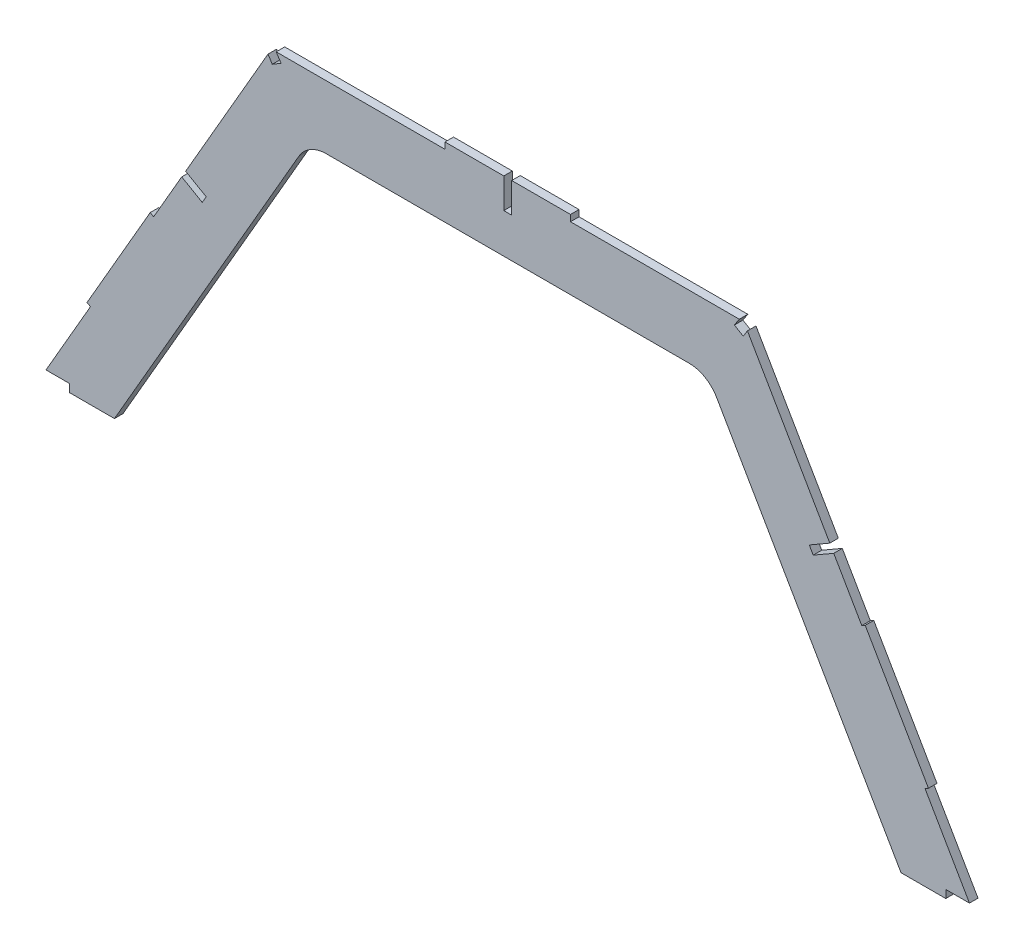
SolidWorks part; units mm, degrees
material "Balsa"
ref_plane "Front Plane" through (0, 0, 0) normal (0, 0, 1) x (1, 0, 0)
ref_plane "Top Plane" through (0, 0, 0) normal (0, 1, 0) x (1, 0, 0)
ref_plane "Right Plane" through (0, 0, 0) normal (1, 0, 0) x (0, 0, -1)
sketch "Sketch1" plane through (0, 0, 0) normal (0, 0, 1) x (1, 0, 0)
  line L0 (-196.85, 0) -> (-63.5, 230.969)
  line L1 (-63.5, 230.969) -> (63.5, 230.969)
  line L2 (63.5, 230.969) -> (196.85, 0)
  line L9 (-167.5206, 0) -> (-48.8353, 205.569)
  line L10 (-48.8353, 205.569) -> (48.8353, 205.569)
  line L11 (48.8353, 205.569) -> (167.5206, 0)
  line L12 (-196.85, 0) -> (-167.5206, 0)
  line L13 (196.85, 0) -> (167.5206, 0)
  line L14 (-174.853, -12.7) -> (-48.8353, 205.569) construction
  line L15 (48.8353, 205.569) -> (174.853, -12.7) construction
  point P14 (0, 205.569)
  dimension "D1" = 127
  dimension "D2" = 120
  dimension "D3" = 25.4
  dimension "D4" = 266.7
  dimension "D5" = 266.7
extrude "Boss-Extrude1" add sketch "Sketch1" along normal blind 3.175 and the other way blind 0.254
fillet "Fillet1" radius 12.7 4 edges at (167.5206, 0, 1.4605) (-167.5206, 0, 1.4605) (48.8353, 205.569, 1.4605) (-48.8353, 205.569, 1.4605)
sketch "Sketch3" plane through (0, 0, -0.254) normal (0, 0, -1) x (-1, 0, 0)
  line L0 (80.264, 201.9329) -> (81.6388, 202.7266)
  line L1 (81.6388, 202.7266) -> (107.0388, 158.7325)
  line L2 (107.0388, 158.7325) -> (105.664, 157.9388)
  line L3 (142.24, 94.5873) -> (143.6148, 95.381)
  line L4 (143.6148, 95.381) -> (169.0148, 51.387)
  line L5 (169.0148, 51.387) -> (167.64, 50.5932)
  line L6 (0, 230.969) -> (0, 176.3712) construction
  line L7 (63.5, 230.969) -> (196.85, 0) construction
  line L8 (25.4, 230.969) -> (-25.4, 230.969)
  line L9 (25.4, 230.969) -> (25.4, 232.5565)
  line L10 (25.4, 232.5565) -> (-25.4, 232.5565)
  line L11 (-25.4, 230.969) -> (-25.4, 232.5565)
  line L12 (80.264, 201.9329) -> (105.664, 157.9388)
  line L13 (167.64, 50.5932) -> (142.24, 94.5873)
  line L16 (-196.85, 0) -> (-174.853, 0)
  line L17 (-163.8544, 6.35) -> (-52.5015, 199.219)
  line L18 (-41.503, 205.569) -> (41.503, 205.569)
  line L19 (52.5015, 199.219) -> (163.8544, 6.35)
  line L20 (174.853, 0) -> (196.85, 0)
  line L21 (196.85, 0) -> (63.5, 230.969)
  line L22 (63.5, 230.969) -> (-63.5, 230.969)
  line L30 (25.4, 230.969) -> (-25.4, 230.969)
  line L42 (-63.5, 230.969) -> (-196.85, 0)
  arc A8 (-174.853, 0) -> (-163.8544, 6.35) centre (-174.853, 12.7) ccw
  arc A9 (-41.503, 205.569) -> (-52.5015, 199.219) centre (-41.503, 192.869) ccw
  arc A10 (52.5015, 199.219) -> (41.503, 205.569) centre (41.503, 192.869) ccw
  arc A11 (163.8544, 6.35) -> (174.853, 0) centre (174.853, 12.7) ccw
  point P30 (0, 230.969)
  dimension "D2" = 1.5875
  dimension "D3" = 33.528
  dimension "D4" = 73.152
  dimension "D5" = 50.8
  dimension "D6" = 50.8
  dimension "D7" = 50.8
  dimension "D8" = 1.5875
  dimension "D1" = 0
extrude "Boss-Extrude2" add sketch "Sketch3" against normal up to surface (3.429 mm away) up to face at (0, 107.0178, 3.175)
sketch "Sketch4" plane through (0, 0, -0.254) normal (0, 0, -1) x (-1, 0, 0)
  line L0 (-63.5, 230.969) -> (-47.853, 203.8675) construction
  line L1 (-61.6669, 230.969) -> (-56.9044, 222.7201)
  line L2 (-63.5, 230.969) -> (-25.4, 230.969) construction
  line L3 (-61.6669, 230.969) -> (-63.5, 230.969)
  line L4 (-64.4165, 229.3815) -> (-63.5, 230.969)
  line L5 (-64.4165, 229.3815) -> (-59.654, 221.1326)
  line L6 (-56.9044, 222.7201) -> (-59.654, 221.1326)
  arc A0 (-41.503, 205.569) -> (-52.5015, 199.219) centre (-41.503, 192.869) ccw construction
  dimension "D1" = 9.525
  dimension "D2" = 1.5875
sketch "Sketch5" plane through (0, 0, -0.254) normal (0, 0, -1) x (-1, 0, 0)
  line L0 (-130.175, 115.4845) -> (-240.9783, 179.4568) construction
  line L1 (-196.85, 0) -> (-63.5, 230.969) construction
  line L2 (-129.3812, 116.8593) -> (-121.1324, 112.0968)
  line L3 (-130.9688, 114.1097) -> (-122.7199, 109.3472)
  line L4 (-121.1324, 112.0968) -> (-122.7199, 109.3472)
  line L5 (-129.3812, 116.8593) -> (-130.9688, 114.1097)
  line L7 (-175.9669, 19.6728) -> (-185.4919, 19.6728)
  line L11 (-185.4919, 19.6728) -> (-187.325, 16.4978)
  line L12 (-175.9669, 19.6728) -> (-175.9669, 16.4978)
  line L13 (-175.9669, 16.4978) -> (-187.325, 16.4978)
  line L14 (-186.309, 16.4978) -> (-195.834, 0)
  line L15 (-174.853, 0) -> (-196.85, 0) construction
  line L16 (-195.834, 0) -> (-196.85, 0)
  line L17 (-187.325, 16.4978) -> (-196.85, 0)
  line L18 (-187.325, 16.4978) -> (-186.309, 16.4978)
  line M5 (-196.85, 0) -> (-174.853, 0)
  line M16 (-63.5, 230.969) -> (-196.85, 0)
  dimension "D1" = 1.5875
  dimension "D2" = 9.525
  dimension "D3" = 19.05
  dimension "D4" = 9.525
  dimension "D5" = 1.016
  dimension "D6" = 3.175
  dimension "D7" = 1.016
extrude "Cut-Extrude1" cut sketch "Sketch5" against normal through all contours L13 L12 L7 M16 | L14 L13 M16 M5 | L4 L2 L5 L3 M16
extrude "Cut-Extrude2" cut sketch "Sketch4" against normal through all
mirror "Mirror1" about plane through (0, 0, 0) normal (1, 0, 0) of "Boss-Extrude2", "Cut-Extrude1", "Cut-Extrude2"
sketch "Sketch6" plane through (0, 0, -0.254) normal (0, 0, -1) x (-1, 0, 0)
  line L0 (-121.3268, 130.81) -> (-91.9974, 130.81)
  line L2 (-174.853, 0) -> (-195.834, 0) construction
  line L3 (-121.3268, 130.81) -> (-105.664, 157.9388)
  line L4 (-129.3813, 116.8593) -> (-105.664, 157.9388) construction
  line L5 (-105.664, 157.9388) -> (-107.0388, 158.7325)
  line L6 (-107.0388, 158.7325) -> (-81.6388, 202.7266)
  line L7 (-81.6388, 202.7266) -> (-80.264, 201.9329)
  line L8 (-80.264, 201.9329) -> (-64.4165, 229.3815)
  line L9 (-64.4165, 229.3815) -> (-59.654, 221.1326)
  line L10 (-59.654, 221.1326) -> (-56.9044, 222.7201)
  line L11 (-56.9044, 222.7201) -> (-61.6669, 230.969)
  line L12 (-61.6669, 230.969) -> (-25.4, 230.969)
  line L13 (-61.6669, 230.969) -> (-25.4, 230.969) construction
  line L15 (-25.4, 232.5565) -> (25.4, 232.5565)
  line L16 (25.4, 232.5565) -> (25.4, 230.969)
  line L17 (25.4, 230.969) -> (61.6669, 230.969)
  line L18 (61.6669, 230.969) -> (56.9044, 222.7201)
  line L19 (56.9044, 222.7201) -> (59.654, 221.1326)
  line L20 (59.654, 221.1326) -> (64.4165, 229.3815)
  line L21 (64.4165, 229.3815) -> (80.264, 201.9329)
  line L22 (80.264, 201.9329) -> (81.6388, 202.7266)
  line L23 (81.6388, 202.7266) -> (107.0388, 158.7325)
  line L24 (107.0388, 158.7325) -> (105.664, 157.9388)
  line L26 (105.664, 157.9388) -> (121.3268, 130.81)
  line L27 (105.664, 157.9388) -> (129.3813, 116.8593) construction
  line L28 (-91.9974, 130.81) -> (-52.5015, 199.219)
  line L29 (-52.5015, 199.219) -> (-41.503, 205.569)
  line L30 (-41.503, 205.569) -> (41.503, 205.569)
  line L31 (41.503, 205.569) -> (47.853, 203.8675)
  line L32 (47.853, 203.8675) -> (52.5015, 199.219)
  line L33 (52.5015, 199.219) -> (91.9974, 130.81)
  line L34 (163.8544, 6.35) -> (52.5015, 199.219) construction
  line L35 (91.9974, 130.81) -> (121.3268, 130.81)
  line L36 (-52.5015, 199.219) -> (-163.8544, 6.35) construction
  line L37 (-25.4, 230.969) -> (-25.4, 232.5565)
  arc A0 (52.5015, 199.219) -> (41.503, 205.569) centre (41.503, 192.869) ccw construction
  dimension "D1" = 130.81
extrude "Cut-Extrude4" cut sketch "Sketch6" against normal through all
sketch "Sketch9" plane through (0, 0, -0.254) normal (0, 0, -1) x (-1, 0, 0)
  line L0 (-91.9974, 130.81) -> (-106.6621, 105.41)
  line L1 (-91.9974, 130.81) -> (-163.8544, 6.35) construction
  line L2 (-106.6621, 105.41) -> (106.6621, 105.41)
  line L3 (163.8544, 6.35) -> (91.9974, 130.81) construction
  line L4 (106.6621, 105.41) -> (91.9974, 130.81)
  line L5 (91.9974, 130.81) -> (-91.9974, 130.81)
  dimension "D1" = 25.4
extrude "Boss-Extrude3" add sketch "Sketch9" against normal blind 3.175
fillet "Fillet2" radius 12.7 2 edges at (-106.6621, 105.41, 1.3335) (106.6621, 105.41, 1.3335)
sketch "Sketch10" plane through (0, 0, -0.254) normal (0, 0, -1) x (-1, 0, 0)
  line L0 (0, 130.81) -> (0, 116.463) construction
  line L1 (-121.3268, 130.81) -> (121.3268, 130.81) construction
  line L2 (-1.5875, 121.285) -> (1.5875, 121.285)
  line L3 (1.5875, 121.285) -> (1.5875, 130.81)
  line L4 (-1.5875, 121.285) -> (-1.5875, 130.81)
  line L5 (-1.5875, 130.81) -> (1.5875, 130.81)
  point P8 (0, 121.285)
  dimension "D1" = 3.175
  dimension "D2" = 9.525
extrude "Cut-Extrude5" cut sketch "Sketch10" against normal up to next contours L5 L3 L2 L4
sketch "Sketch11" [suppressed] plane through (0, 0, 0) normal (0, 0, -1) x (-1, 0, 0)
  line L0 (0, 232.5565) -> (0, 212.8922) construction
  line L2 (-1.5875, 223.0315) -> (1.5875, 223.0315)
  line L3 (-1.5875, 223.0315) -> (-1.5875, 232.5565)
  line L4 (25.4, 232.5565) -> (-25.4, 232.5565) construction
  line L5 (-1.5875, 232.5565) -> (1.5875, 232.5565)
  line L6 (1.5875, 232.5565) -> (1.5875, 223.0315)
  point P6 (0, 223.0315)
  dimension "D1" = 3.175
  dimension "D2" = 9.525
extrude "Cut-Extrude6" [suppressed] cut sketch "Sketch11" against normal up to next
sketch "Sketch12" plane through (0, 130.81, 0) normal (0, 1, 0) x (1, 0, 0)
  line L0 (91.9974, -2.921) -> (1.5875, -2.921) construction
  line L1 (1.5875, 0.254) -> (25.2095, 0.254)
  line L2 (1.5875, 0.254) -> (1.5875, -2.921)
  line L3 (1.5875, -2.921) -> (25.2095, -2.921)
  line L4 (25.2095, 0.254) -> (25.2095, -2.921)
  line L5 (-1.5875, -2.921) -> (-91.9974, -2.921) construction
  line L6 (-1.5875, 0.254) -> (-25.2095, 0.254)
  line L7 (-1.5875, 0.254) -> (-1.5875, -2.921)
  line L8 (-1.5875, -2.921) -> (-25.2095, -2.921)
  line L9 (-25.2095, 0.254) -> (-25.2095, -2.921)
  dimension "D1" = 23.622
  dimension "D2" = 23.622
extrude "Boss-Extrude4" add sketch "Sketch12" along normal blind 2.54
sketch "Sketch14" plane through (0, 0, -0.254) normal (0, 0, -1) x (-1, 0, 0)
  line L0 (121.3918, 125.5218) -> (118.5256, 126.591)
  line L2 (121.3268, 130.81) -> (122.8652, 128.1455)
  line L7 (0, 121.285) -> (0, 133.5135) construction
  line L8 (-1.5875, 121.285) -> (1.5875, 121.285) construction
  line L13 (121.3268, 130.81) -> (129.3813, 116.8593) construction
  line L14 (122.8652, 128.1455) -> (121.3918, 125.5218)
  line L19 (117.7976, 127.852) -> (117.7976, 130.81)
  line L20 (117.7976, 127.852) -> (118.5256, 126.591)
  line L21 (117.7976, 130.81) -> (121.3268, 130.81)
  line L22 (-117.7976, 130.81) -> (-121.3268, 130.81)
  line L23 (-117.7976, 127.852) -> (-118.5256, 126.591)
  line L24 (-117.7976, 127.852) -> (-117.7976, 130.81)
  line L25 (-122.8652, 128.1455) -> (-121.3918, 125.5218)
  line L26 (-121.3268, 130.81) -> (-122.8652, 128.1455)
  line L27 (-121.3918, 125.5218) -> (-118.5256, 126.591)
  dimension "D1" = 3.5292
  dimension "D2" = 2.6459
  dimension "D3" = 5.2882
  dimension "D4" = 120.684
  dimension "D5" = 3.0591
  dimension "D6" = 98.859
extrude "Cut-Extrude7" [suppressed] cut sketch "Sketch14" against normal up to next
sketch "Sketch15" plane through (0, 0, -0.254) normal (0, 0, -1) x (-1, 0, 0)
  line L1 (-227.3304, 16.4978) -> (236.5896, 16.4978)
  line L2 (-227.3304, 16.4978) -> (-227.3304, -10.1157)
  line L3 (-227.3304, -10.1157) -> (236.5896, -10.1157)
  line L4 (236.5896, 16.4978) -> (236.5896, -10.1157)
extrude "Cut-Extrude8" cut sketch "Sketch15" against normal through all
sketch "Sketch16" plane through (0, 0, -0.254) normal (0, 0, -1) x (-1, 0, 0)
  line L0 (-121.3268, 130.81) -> (-94.8971, 176.5876)
  line L1 (-129.3813, 116.8593) -> (-121.3268, 130.81) construction
  line L2 (121.3268, 130.81) -> (94.8971, 176.5876)
  line L3 (121.3268, 130.81) -> (129.3813, 116.8593) construction
  line L4 (-94.8971, 176.5876) -> (94.8971, 176.5876)
  line L5 (-91.9974, 130.81) -> (-80.2324, 151.1876)
  line L6 (-121.3268, 130.81) -> (-25.2095, 130.81) construction
  line L7 (-80.2324, 151.1876) -> (80.2324, 151.1876)
  line L8 (80.2324, 151.1876) -> (91.9974, 130.81)
  line L9 (25.2095, 130.81) -> (121.3268, 130.81) construction
  line L10 (-121.3268, 130.81) -> (-91.9974, 130.81)
  line L11 (91.9974, 130.81) -> (121.3268, 130.81)
  line L12 (-110.3283, 99.06) -> (-157.9956, 16.4978) construction
  line L13 (157.9956, 16.4978) -> (110.3283, 99.06) construction
  point P14 (0, 0)
  point P20 (122.8652, 128.1455)
  point P21 (0, 0)
  dimension "D1" = 25.4
extrude "Boss-Extrude5" add sketch "Sketch16" against normal up to vertex (3.429 mm away)
sketch "Sketch17" plane through (0, 0, -0.254) normal (0, 0, -1) x (-1, 0, 0)
  line L0 (-1.5875, 176.5876) -> (-1.5875, 179.1276)
  line L1 (94.8971, 176.5876) -> (-94.8971, 176.5876) construction
  line L2 (-1.5875, 179.1276) -> (-25.2095, 179.1276)
  line L3 (-25.2095, 179.1276) -> (-25.2095, 176.5876)
  line L4 (-25.2095, 176.5876) -> (-1.5875, 176.5876)
  line L5 (-25.2095, 133.35) -> (-25.2095, 130.81) construction
  line L6 (-1.5875, 121.285) -> (-1.5875, 133.35) construction
  line L7 (0, 121.285) -> (0, 193.185) construction
  line L9 (25.2095, 176.5876) -> (1.5875, 176.5876)
  line L10 (25.2095, 179.1276) -> (25.2095, 176.5876)
  line L11 (1.5875, 179.1276) -> (25.2095, 179.1276)
  line L12 (1.5875, 176.5876) -> (1.5875, 179.1276)
  dimension "D1" = 2.54
extrude "Boss-Extrude6" add sketch "Sketch17" against normal up to vertex (3.429 mm away)
sketch "Sketch18" plane through (0, 176.5876, 0) normal (0, 1, 0) x (1, 0, 0)
  line L0 (-1.5875, -3.175) -> (1.5875, -3.175) construction
  line L1 (1.5875, -3.175) -> (-1.5875, -3.175)
  line L2 (1.5875, -3.175) -> (1.5875, 0.254)
  line L3 (1.5875, 0.254) -> (-1.5875, 0.254)
  line L4 (-1.5875, -3.175) -> (-1.5875, 0.254)
  point P4 (0, 0)
  point P5 (1.5875, 0.9795)
  point P9 (-1.5875, 0.254)
  point P11 (-1.5875, -3.175)
extrude "Cut-Extrude9" cut sketch "Sketch18" against normal blind 9.525
sketch "Sketch19" plane through (0, 0, -0.254) normal (0, 0, -1) x (-1, 0, 0)
  line L0 (-134.1619, 57.7789) -> (-86.1149, 140.9988)
  line L1 (-110.3283, 99.06) -> (-157.9956, 16.4978) construction
  line L2 (-91.9974, 130.81) -> (-80.2324, 151.1876) construction
  line L3 (-86.1149, 140.9988) -> (86.1149, 140.9988)
  line L4 (80.2324, 151.1876) -> (91.9974, 130.81) construction
  line L5 (86.1149, 140.9988) -> (134.1619, 57.7789)
  line L6 (157.9956, 16.4978) -> (110.3283, 99.06) construction
  line L7 (134.1619, 57.7789) -> (-134.1619, 57.7789)
  point P6 (-134.1619, 57.7789)
  point P13 (-86.1149, 140.9988)
extrude "Cut-Extrude10" cut sketch "Sketch19" against normal through all contours L7 L0 L3 L5
fillet "Fillet3" radius 12.7 2 edges at (-80.2324, 151.1876, 1.4605) (80.2324, 151.1876, 1.4605)
sketch "Sketch20" plane through (0, 0, -0.254) normal (0, 0, -1) x (-1, 0, 0)
  line L0 (93.019, 176.5876) -> (91.0602, 173.5744)
  line L1 (94.8971, 176.5876) -> (25.2095, 176.5876) construction
  line L2 (91.0602, 173.5744) -> (94.6014, 171.4599)
  line L3 (94.6014, 171.4599) -> (96.297, 174.1629)
  line L4 (94.8971, 176.5876) -> (129.3813, 116.8593) construction
  line L5 (93.019, 176.5876) -> (94.8971, 176.5876)
  line L6 (94.8971, 176.5876) -> (96.297, 174.1629)
  line L7 (0, 167.0626) -> (0, 171.6774) construction
  line L9 (-94.8971, 176.5876) -> (-96.297, 174.1629)
  line L10 (-93.019, 176.5876) -> (-94.8971, 176.5876)
  line L11 (-94.6014, 171.4599) -> (-96.297, 174.1629)
  line L12 (-91.0602, 173.5744) -> (-94.6014, 171.4599)
  line L13 (-93.019, 176.5876) -> (-91.0602, 173.5744)
extrude "Cut-Extrude11" cut sketch "Sketch20" against normal through all
